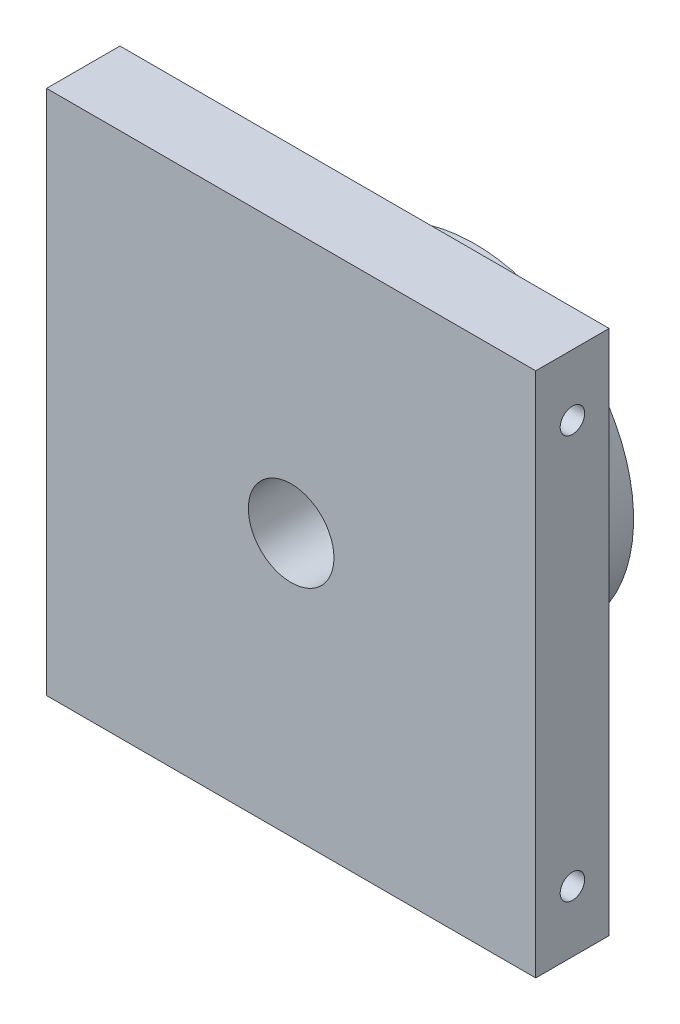
SolidWorks part; units mm, degrees
ref_plane "前视基准面" through (0, 0, 0) normal (0, 0, 1) x (1, 0, 0)
ref_plane "上视基准面" through (0, 0, 0) normal (0, 1, 0) x (1, 0, 0)
ref_plane "右视基准面" through (0, 0, 0) normal (1, 0, 0) x (0, 0, -1)
sketch "草图1" plane through (0, 0, 0) normal (0, 0, 1) x (1, 0, 0)
  line L1 (-20, -21.5) -> (20, -21.5)
  line L2 (-20, -21.5) -> (-20, 21.5)
  line L3 (-20, 21.5) -> (20, 21.5)
  line L4 (20, -21.5) -> (20, 21.5)
  line L5 (-20, -21.5) -> (20, 21.5) construction
  line L6 (-20, 21.5) -> (20, -21.5) construction
  circle A0 centre (0, 0) radius 1.5
  point P0 (0, 0)
  dimension "D2" = 3
  dimension "D1" = 43
  dimension "D3" = 40
extrude "凸台-拉伸1" add sketch "草图1" along normal blind 6
sketch "草图2" plane through (20, 0, 0) normal (1, 0, 0) x (0, 0, -1)
  line L0 (-3, 21.5) -> (-3, -21.5)
  line L1 (-6, 21.5) -> (0, 21.5) construction
  line L2 (-6, -21.5) -> (0, -21.5) construction
  circle A0 centre (-3, 16.5) radius 1
  circle A1 centre (-3, -16.5) radius 1
  dimension "D1" = 2
  dimension "D2" = 2
  dimension "D3" = 5
  dimension "D4" = 5
extrude "切除-拉伸1" cut sketch "草图2" against normal through all contours L0 A0 | L0 A0 | L0 A1 | L0 A1
sketch "草图3" plane through (0, 0, 0) normal (0, 0, -1) x (-1, 0, 0)
  circle A0 centre (0, 0) radius 13
  dimension "D1" = 26
extrude "凸台-拉伸2" add sketch "草图3" along normal blind 4
sketch "草图4" plane through (0, 0, -4) normal (0, 0, -1) x (-1, 0, 0)
  circle A0 centre (0, 0) radius 13
  circle A1 centre (0, 0) radius 12.2
  dimension "D1" = 24.4
extrude "凸台-拉伸3" add sketch "草图4" along normal blind 5
sketch "草图5" plane through (0, 0, 6) normal (0, 0, 1) x (1, 0, 0)
  circle A0 centre (0, 0) radius 3.5
  dimension "D1" = 7
extrude "切除-拉伸2" cut sketch "草图5" against normal through all
